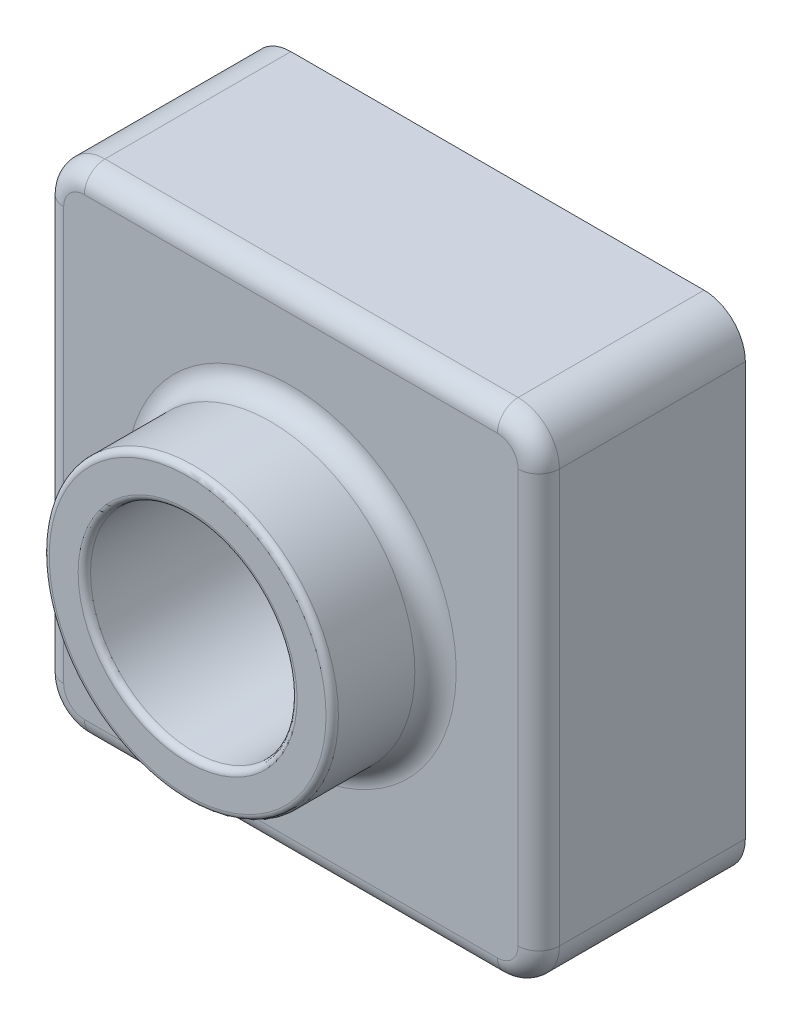
SolidWorks part; units mm, degrees
material "Chrome Stainless Steel"
ref_plane "Front Plane" through (0, 0, 0) normal (0, 0, 1) x (1, 0, 0)
ref_plane "Top Plane" through (0, 0, 0) normal (0, 1, 0) x (1, 0, 0)
ref_plane "Right Plane" through (0, 0, 0) normal (1, 0, 0) x (0, 0, -1)
sketch "Sketch1" plane through (0, 0, 0) normal (0, 0, 1) x (1, 0, 0)
  line L1 (0, 0) -> (120, 0)
  line L2 (0, 0) -> (0, 120)
  line L3 (0, 120) -> (120, 120)
  line L4 (120, 0) -> (120, 120)
  dimension "D1" = 120
  dimension "D2" = 120
extrude "Boss-Extrude1" add sketch "Sketch1" along normal blind 50
sketch "Sketch2" plane through (0, 0, 50) normal (0, 0, 1) x (1, 0, 0)
  line L0 (120, 120) -> (0, 120) construction
  line L1 (120, 0) -> (120, 120) construction
  circle A0 centre (60, 60) radius 35
  dimension "D1" = 70
  dimension "D2" = 60
  dimension "D3" = 60
extrude "Boss-Extrude2" add sketch "Sketch2" along normal blind 25
sketch "Sketch3" plane through (0, 0, 75) normal (0, 0, 1) x (1, 0, 0)
  circle A0 centre (60, 60) radius 25
  dimension "D1" = 50
extrude "Cut-Extrude1" cut sketch "Sketch3" against normal through all
fillet "Fillet1" radius 10 4 edges at (0, 120, 25) (120, 0, 25) (120, 120, 25) (0, 0, 25)
fillet "Fillet2" radius 1.5 2 edges at (95, 60, 75) (85, 60, 75)
fillet "Fillet3" radius 5 9 edges at (117.0711, 117.0711, 50) (120, 60, 50) (117.0711, 2.9289, 50) (60, 0, 50) (0, 60, 50) (2.9289, 117.0711, 50) (60, 120, 50) (95, 60, 50) (2.9289, 2.9289, 50)
shell "Shell1" thickness 2
